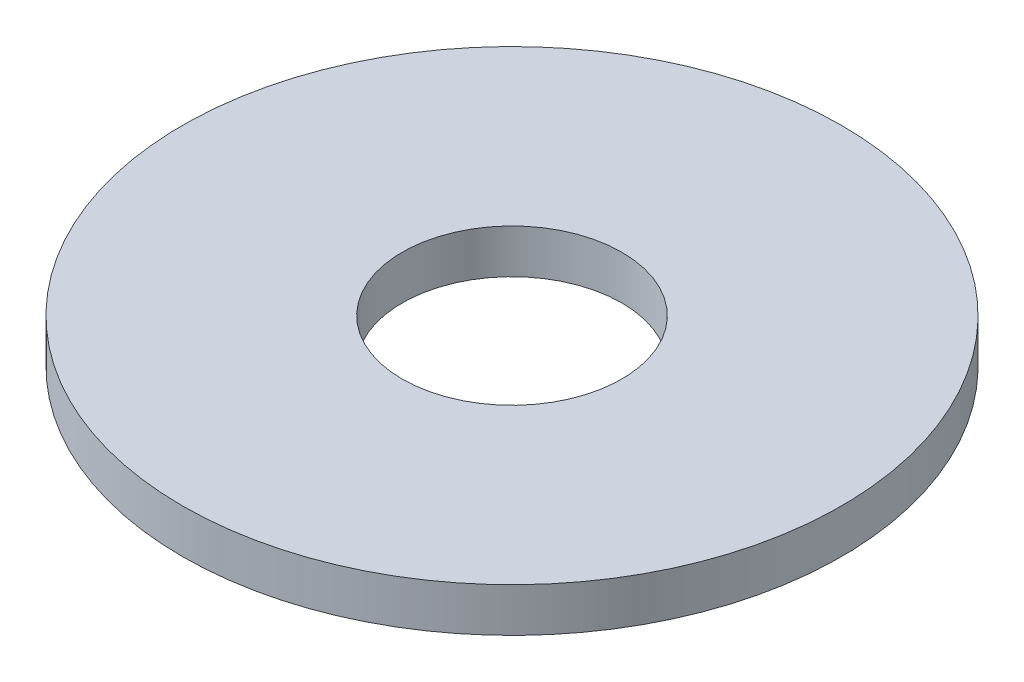
SolidWorks part; units mm, degrees
material "Cast Alloy Steel"
ref_plane "Front Plane" through (0, 0, 0) normal (0, 0, 1) x (1, 0, 0)
ref_plane "Top Plane" through (0, 0, 0) normal (0, 1, 0) x (1, 0, 0)
ref_plane "Right Plane" through (0, 0, 0) normal (1, 0, 0) x (0, 0, -1)
sketch "Sketch1" plane through (0, 0, 0) normal (0, 1, 0) x (1, 0, 0)
  circle A0 centre (0, 0) radius 5
  circle A1 centre (0, 0) radius 15
  dimension "D1" = 30
  dimension "D2" = 10
extrude "Boss-Extrude1" add sketch "Sketch1" along normal mid plane 2
